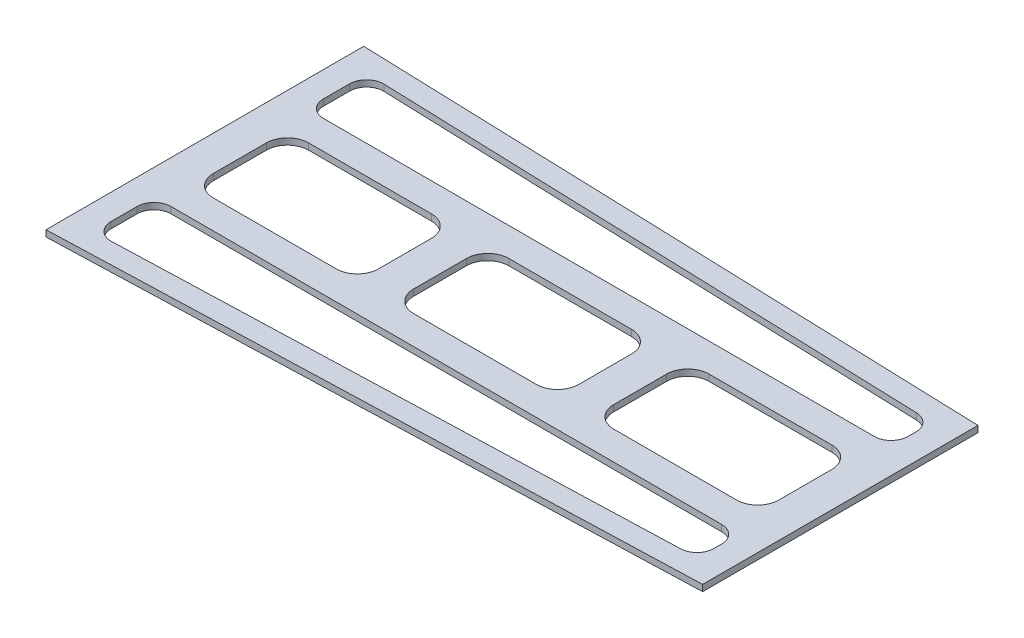
SolidWorks part; units mm, degrees
ref_plane "Front Plane" through (0, 0, 0) normal (0, 0, 1) x (1, 0, 0)
ref_plane "Top Plane" through (0, 0, 0) normal (0, 1, 0) x (1, 0, 0)
ref_plane "Right Plane" through (0, 0, 0) normal (1, 0, 0) x (0, 0, -1)
sketch "Sketch1" plane through (0, 0, 0) normal (0, 1, 0) x (1, 0, 0)
  line L0 (0, 0) -> (0, 75)
  line L7 (0, 75) -> (300, 65)
  line L8 (300, 65) -> (300, 0)
  line L9 (300, 0) -> (0, 0)
  point P0 (0, 0)
  dimension "D4" = 300
  dimension "D5" = 75
  dimension "D6" = 65
extrude "Boss-Extrude1" add sketch "Sketch1" along normal blind 3
mirror "Mirror1" of "Boss-Extrude1"
sketch "Sketch2" plane through (0, 3, 0) normal (0, 1, 0) x (1, 0, 0)
  line L0 (0, -1.65) -> (0, 1.65) construction
  line L1 (0, 31) -> (300, 31) construction
  line L2 (0, 31) -> (0, -31) construction
  line L3 (0, -31) -> (300, -31) construction
  line L4 (300, 31) -> (300, -31) construction
  line L5 (300, -65) -> (300, 65) construction
  line L6 (-1.65, 0) -> (1.65, 0) construction
  line L7 (55.5, 0) -> (150, 0) construction
  line L8 (94.5, -22.5) -> (16.5, -22.5)
  line L9 (94.5, -22.5) -> (94.5, 22.5)
  line L10 (94.5, 22.5) -> (16.5, 22.5)
  line L11 (16.5, -22.5) -> (16.5, 22.5)
  line L12 (94.5, -22.5) -> (16.5, 22.5) construction
  line L13 (94.5, 22.5) -> (16.5, -22.5) construction
  line L14 (189, -22.5) -> (111, -22.5)
  line L15 (189, -22.5) -> (189, 22.5)
  line L16 (189, 22.5) -> (111, 22.5)
  line L17 (111, -22.5) -> (111, 22.5)
  line L18 (189, -22.5) -> (111, 22.5) construction
  line L19 (189, 22.5) -> (111, -22.5) construction
  line L20 (283.5, -22.5) -> (205.5, -22.5)
  line L21 (283.5, -22.5) -> (283.5, 22.5)
  line L22 (283.5, 22.5) -> (205.5, 22.5)
  line L23 (205.5, -22.5) -> (205.5, 22.5)
  line L24 (283.5, -22.5) -> (205.5, 22.5) construction
  line L25 (283.5, 22.5) -> (205.5, -22.5) construction
  line L26 (150, 0) -> (244.5, 0) construction
  line L27 (0, 0) -> (55.5, 0) construction
  line L28 (244.5, 0) -> (300, 0) construction
  line L29 (16.5, -22.5) -> (0, -22.5) construction
  line L30 (94.5, -22.5) -> (111, -22.5) construction
  point P8 (0, 0)
  point P11 (55.5, 0)
  point P16 (150, 0)
  point P21 (244.5, 0)
  dimension "D1" = 62
  dimension "D2" = 45
  dimension "D3" = 78
extrude "Cut-Extrude1" cut sketch "Sketch2" against normal blind 10
fillet "Fillet1" radius 10 12 edges at (283.5, 1.5, 22.5) (94.5, 1.5, 22.5) (189, 1.5, 22.5) (94.5, 1.5, -22.5) (189, 1.5, -22.5) (283.5, 1.5, -22.5) (205.5, 1.5, 22.5) (111, 1.5, 22.5) (16.5, 1.5, 22.5) (16.5, 1.5, -22.5) (111, 1.5, -22.5) (205.5, 1.5, -22.5)
sketch "Sketch3" plane through (0, 3, 0) normal (0, 1, 0) x (1, 0, 0)
  line L0 (-1.65, 0) -> (1.65, 0) construction
  line L1 (-87.6274, -30) -> (294.5978, -30) construction
  line L2 (-87.6274, -30) -> (-87.6274, 30) construction
  line L3 (-87.6274, 30) -> (294.5978, 30) construction
  line L4 (294.5978, -30) -> (294.5978, 30) construction
  line L5 (-87.6274, -30) -> (294.5978, 30) construction
  line L6 (-87.6274, 30) -> (294.5978, -30) construction
  line L7 (12, 56.3233) -> (12, 44)
  line L8 (20, 36) -> (280, 36)
  line L9 (288, 44) -> (288, 47.6567)
  line L10 (280.2665, 55.6522) -> (20.2665, 64.3189)
  line L11 (0, -1.65) -> (0, 1.65) construction
  line L12 (300, -65) -> (300, 65) construction
  line L13 (300, 65) -> (0, 75) construction
  arc A0 (288, 47.6567) -> (280.2665, 55.6522) centre (280, 47.6567) ccw
  arc A1 (280, 36) -> (288, 44) centre (280, 44) ccw
  arc A2 (12, 44) -> (20, 36) centre (20, 44) ccw
  arc A3 (12, 56.3233) -> (20.2665, 64.3189) centre (20, 56.3233) cw
  point P0 (103.4852, 0)
  dimension "D6" = 8
  dimension "D1" = 60
  dimension "D2" = 12
  dimension "D3" = 12
  dimension "D4" = 10
  dimension "D5" = 6
extrude "Cut-Extrude2" cut sketch "Sketch3" against normal blind 10
mirror "Mirror2" about plane through (0, 0, 0) normal (0, 0, 1) of "Cut-Extrude2"
